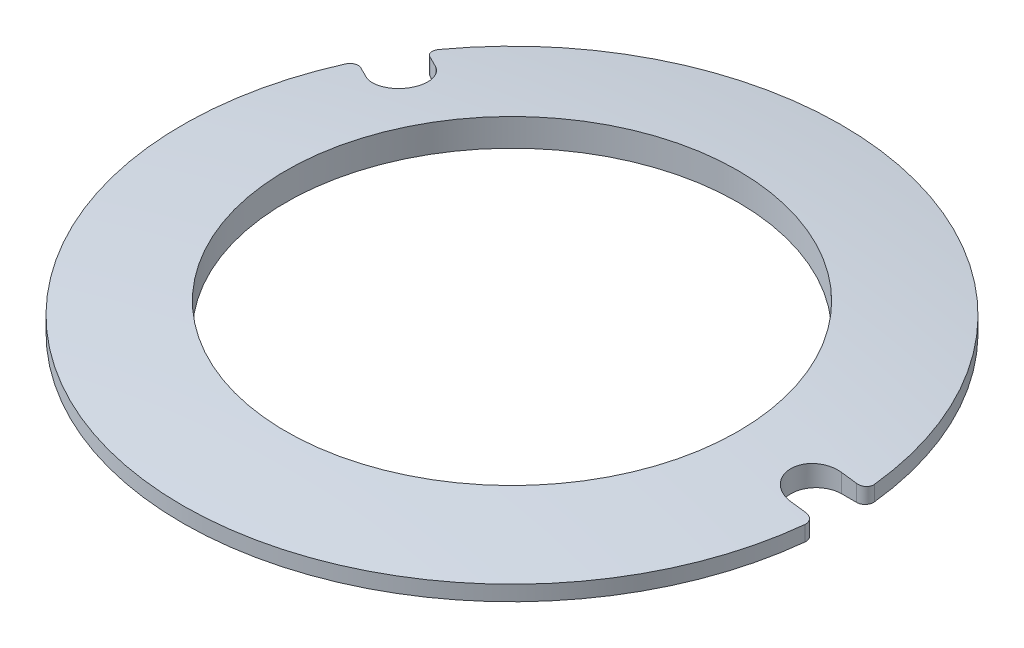
SolidWorks part; units mm, degrees
ref_plane "Front" through (0, 0, 0) normal (0, 0, 1) x (1, 0, 0)
ref_plane "Top" through (0, 0, 0) normal (0, 1, 0) x (1, 0, 0)
ref_plane "Right" through (0, 0, 0) normal (1, 0, 0) x (0, 0, -1)
sketch "Sketch1" plane through (0, 0, 0) normal (0, 0, 1) x (1, 0, 0)
  line L0 (0, 0) -> (0, 278.75) construction
  line L1 (39, 0) -> (39, 278.75) construction
  line L2 (39, 274.2083) -> (26.75, 274.2083)
  line L3 (0, 274.2083) -> (0, 278.75) construction
  line L4 (39, 276.0083) -> (39, 274.2083)
  line L5 (26.75, 277.4635) -> (26.75, 274.2083)
  line L7 (26.75, 274.2083) -> (0, 274.2083) construction
  arc A0 (39, 276.0083) -> (26.75, 277.4635) centre (0, 0) ccw
  arc A1 (26.75, 277.4635) -> (0, 278.75) centre (0, 0) ccw construction
  dimension "D3" = 1.8
  dimension "D1" = 278.75
  dimension "D4" = 26.75
  dimension "D2" = 39
revolve "Revolve1" add sketch "Sketch1" angle 360 about L0
sketch "Sketch2" plane through (0, 0, 0) normal (0, 1, 0) x (1, 0, 0)
  line L0 (36, 0) -> (46, 0) construction
  line L1 (36, 3) -> (46, 3)
  line L2 (36, -3) -> (46, -3)
  line L3 (-31.1769, 18) -> (-39.8372, 23) construction
  line L4 (-32.6769, 15.4019) -> (-41.3372, 20.4019)
  line L5 (-29.6769, 20.5981) -> (-38.3372, 25.5981)
  line L6 (0, 0) -> (36, 0) construction
  line L7 (0, 0) -> (-31.1769, 18) construction
  arc A2 (36, 3) -> (36, -3) centre (36, 0) ccw
  arc A3 (46, -3) -> (46, 3) centre (46, 0) ccw
  arc A4 (-32.6769, 15.4019) -> (-29.6769, 20.5981) centre (-31.1769, 18) ccw
  arc A5 (-38.3372, 25.5981) -> (-41.3372, 20.4019) centre (-39.8372, 23) ccw
  point P2 (41, 0)
  point P13 (-35.507, 20.5)
  dimension "D1" = 6
  dimension "D3" = 150
  dimension "D4" = 36
  dimension "D2" = 10
extrude "Cut-Extrude2" cut sketch "Sketch2" along normal through all
fillet "Fillet1" radius 1 4 edges at (-35.1749, 275.1083, -16.8441) (-32.1749, 275.1083, -22.0403) (38.8844, 275.1083, 3) (38.8844, 275.1083, -3)
